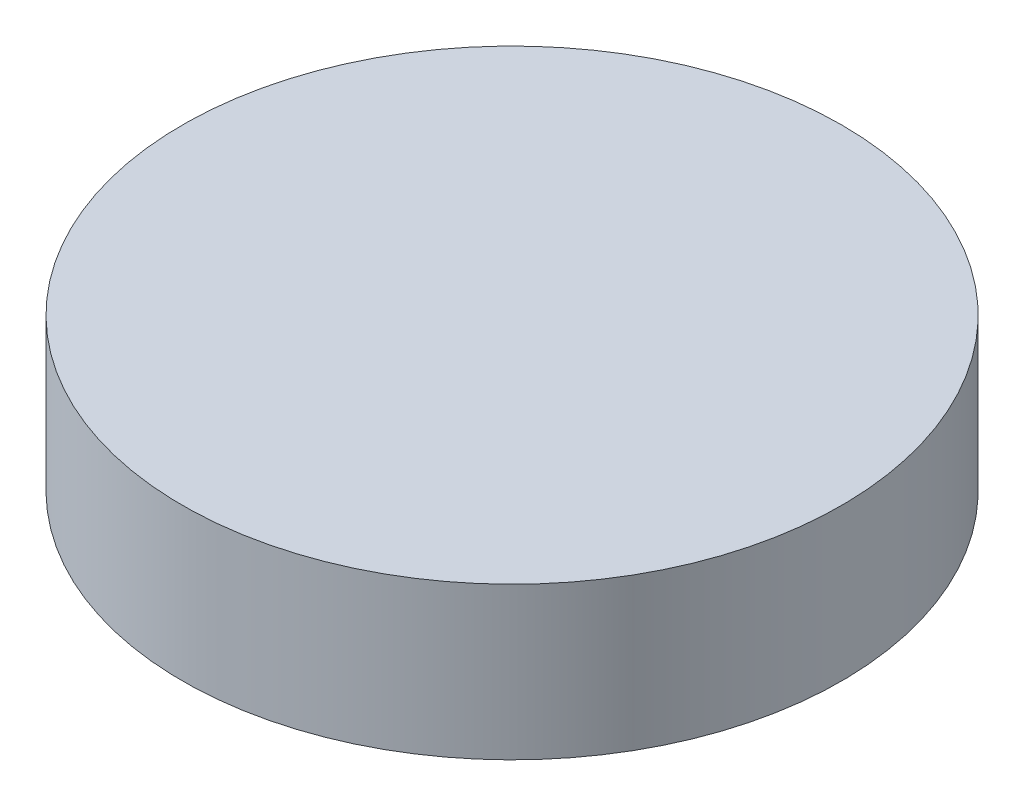
SolidWorks part; units mm, degrees
ref_plane "Front Plane" through (0, 0, 0) normal (0, 0, 1) x (1, 0, 0)
ref_plane "Top Plane" through (0, 0, 0) normal (0, 1, 0) x (1, 0, 0)
ref_plane "Right Plane" through (0, 0, 0) normal (1, 0, 0) x (0, 0, -1)
sketch "Sketch1" plane through (0, 0, 0) normal (0, 1, 0) x (1, 0, 0)
  circle A0 centre (0, 0) radius 16.51
  dimension "D1" = 33.02
extrude "Boss-Extrude1" add sketch "Sketch1" along normal blind 7.62
